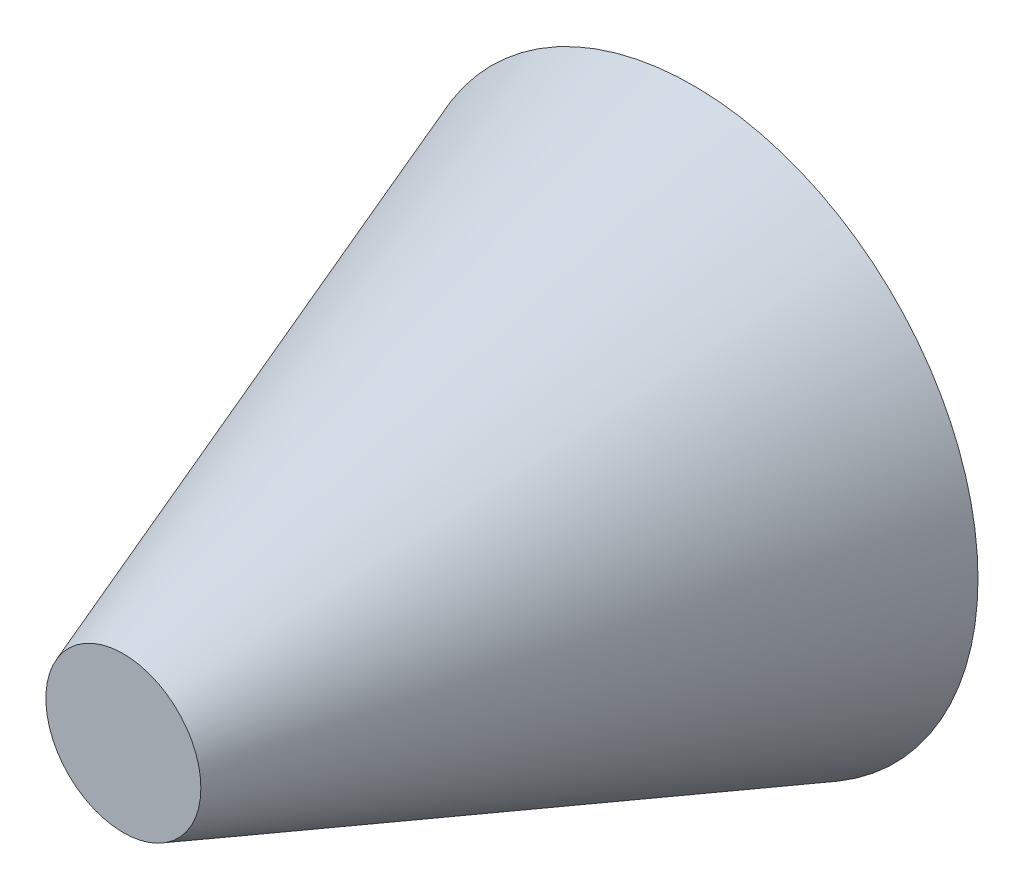
SolidWorks part; units mm, degrees
ref_plane "Front Plane" through (0, 0, 0) normal (0, 0, 1) x (1, 0, 0)
ref_plane "Top Plane" through (0, 0, 0) normal (0, 1, 0) x (1, 0, 0)
ref_plane "Right Plane" through (0, 0, 0) normal (1, 0, 0) x (0, 0, -1)
sketch "Sketch1" plane through (0, 0, 0) normal (0, 0, 1) x (1, 0, 0)
  circle A0 centre (0, 0) radius 508
  dimension "D1" = 1016
extrude "Boss-Extrude1" add sketch "Sketch1" along normal blind 1016 draft 20
